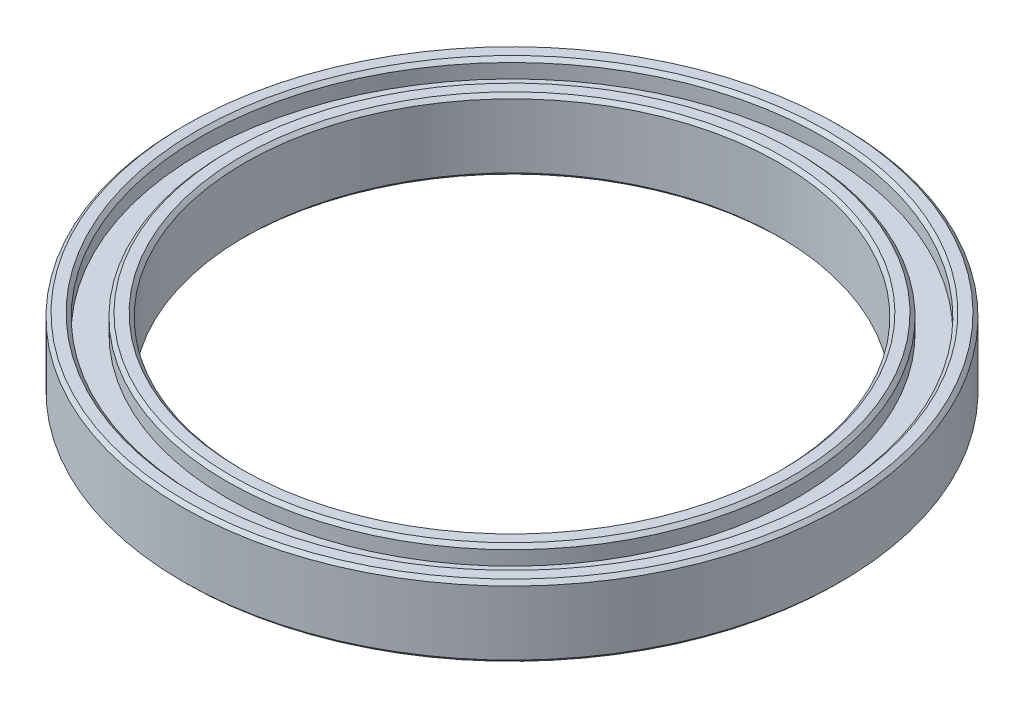
SolidWorks part; units mm, degrees
ref_plane "Front Plane" through (0, 0, 0) normal (0, 0, 1) x (1, 0, 0)
ref_plane "Top Plane" through (0, 0, 0) normal (0, 1, 0) x (1, 0, 0)
ref_plane "Right Plane" through (0, 0, 0) normal (1, 0, 0) x (0, 0, -1)
sketch "Sketch1" plane through (0, 0, 0) normal (0, 1, 0) x (1, 0, 0)
  circle A0 centre (0, 0) radius 18.5
  circle A1 centre (0, 0) radius 15
  dimension "D1" = 37
  dimension "D2" = 30
extrude "Boss-Extrude1" add sketch "Sketch1" along normal blind 4
sketch "Sketch2" plane through (0, 4, 0) normal (0, 1, 0) x (1, 0, 0)
  circle A0 centre (0, 0) radius 16
  circle A1 centre (0, 0) radius 17.5
  dimension "D1" = 35
  dimension "D2" = 32
extrude "Cut-Extrude1" cut sketch "Sketch2" against normal blind 1
sketch "Sketch3" plane through (0, 0, 0) normal (0, -1, 0) x (1, 0, 0)
  circle A0 centre (0, 0) radius 16
  circle A1 centre (0, 0) radius 17.5
  dimension "D1" = 35
  dimension "D2" = 32
extrude "Cut-Extrude2" cut sketch "Sketch3" against normal blind 1
chamfer "Chamfer1" distance 0.2 angle 45 8 edges at (0, 4, 16) (0, 4, 15) (0, 4, 18.5) (0, 4, 17.5) (0, 0, 18.5) (0, 0, -17.5) (0, 0, -16) (0, 0, 15)
